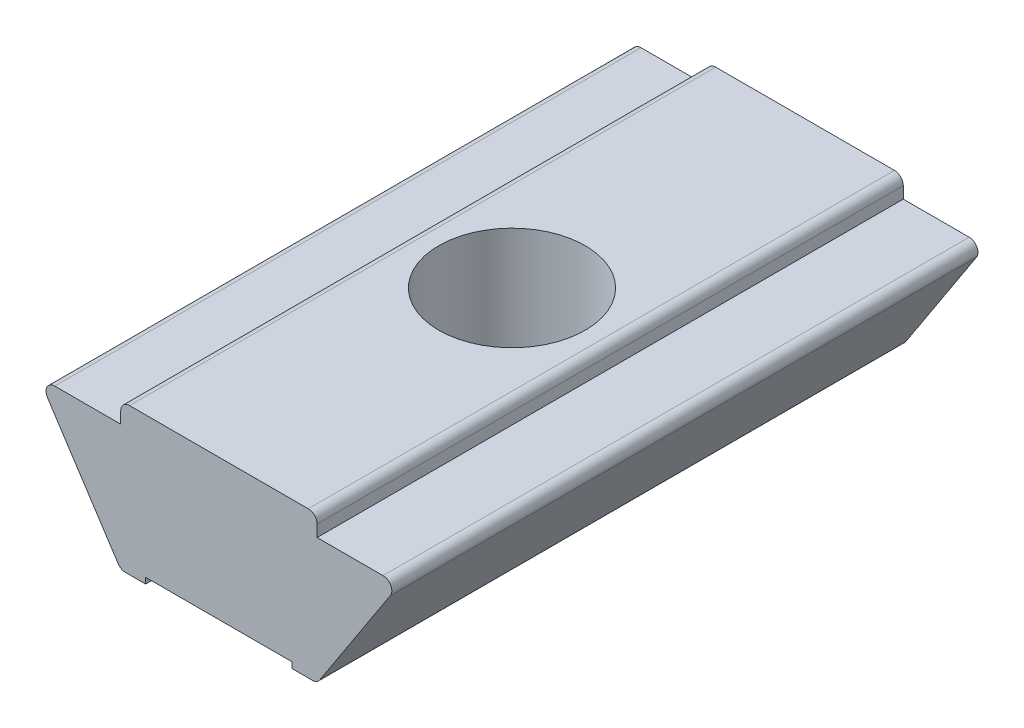
SolidWorks part; units mm, degrees
ref_plane "前视基准面" through (0, 0, 0) normal (0, 0, 1) x (1, 0, 0)
ref_plane "上视基准面" through (0, 0, 0) normal (0, 1, 0) x (1, 0, 0)
ref_plane "右视基准面" through (0, 0, 0) normal (1, 0, 0) x (0, 0, -1)
sketch "草图1" plane through (0, 0, 0) normal (0, 0, 1) x (1, 0, 0)
  line B0 (-0.1625, 4.7) -> (-0.1625, 4.3)
  line B1 (6.5375, 4.7) -> (6.5375, 4.3)
  line B2 (6.2375, 5) -> (0.1375, 5)
  line B3 (0, 0) -> (6.3749, 0)
  line B4 (-2.4125, 4.3) -> (-0.1625, 4.3)
  line B5 (6.5375, 4.3) -> (8.7875, 4.3)
  line B6 (-0.2513, 0.1362) -> (-2.6706, 3.847)
  line B7 (6.6262, 0.1362) -> (9.0455, 3.847)
  arc B8 (6.5375, 4.7) -> (6.2375, 5) centre (6.2375, 4.7) ccw
  arc B9 (0.1375, 5) -> (-0.1625, 4.7) centre (0.1375, 4.7) ccw
  arc B10 (-0.2513, 0.1362) -> (0, 0) centre (0, 0.3) ccw
  arc B11 (-2.4125, 4.3) -> (-2.6706, 3.847) centre (-2.4125, 4) ccw
  arc B12 (6.3749, 0) -> (6.6262, 0.1362) centre (6.3749, 0.3) ccw
  arc B13 (9.0455, 3.847) -> (8.7875, 4.3) centre (8.7875, 4) ccw
sketch_block_instance "A$C4175101B-1"
sketch_block "A$C4175101B"
extrude "凸台-拉伸1" add sketch "草图1" along normal mid plane 20
sketch "草图3" plane through (0, 5, 0) normal (0, 1, 0) x (1, 0, 0)
  line L0 (6.2375, 10) -> (0.1375, 10) construction
  point P0 (3.1875, 0)
  dimension "D1" = 10
hole_wizard "M6 螺纹孔1" positions "3D草图1" profile "草图4" tap size "M6" standard "Iso" end condition through all
sketch3d "3D草图1"
  point P0 (3.1875, 5, 0)
sketch "草图4" plane through (3.1875, 5, 0) normal (1, 0, 0) x (0, 0, 1)
  line L0 (0, 0) -> (0, 5)
  line L1 (0, 5) -> (2.5, 5)
  line L2 (2.5, 5) -> (2.5, 0)
  line L5 (2.5, 0) -> (0, 0)
  line L11 (0, -6.35) -> (0, 107.95) construction
  dimension "通孔螺纹孔钻头直径" = 5
  dimension "通孔螺纹孔钻头深度" = 5
cosmetic thread "孔螺蚊线1" parameters "D2"=6
sketch "草图5" plane through (0, 0, 10) normal (0, 0, 1) x (1, 0, 0)
  line L0 (0, 0) -> (6.3749, 0) construction
  line L1 (0.6875, 0) -> (5.6875, 0)
  line L2 (0.6875, 0) -> (0.6875, 0.2)
  line L3 (0.6875, 0.2) -> (5.6875, 0.2)
  line L4 (5.6875, 0) -> (5.6875, 0.2)
  line L5 (3.1875, 5) -> (3.1875, 0.2) construction
  line L6 (6.2375, 5) -> (0.1375, 5) construction
  dimension "D1" = 5
  dimension "D2" = 0.2
extrude "切除-拉伸1" cut sketch "草图5" against normal blind 10
ref_plane "基准面2" through (3.1875, 0, 0) normal (-1, 0, 0) x (0, 0, 1)
sketch "草图6" plane through (3.1875, 0, 0) normal (-1, 0, 0) x (0, 0, 1)
  line L0 (3.0032, 0.2) -> (-2.9988, -2.5)
  line L1 (0, 0.2) -> (10, 0.2) construction
  line L2 (10, 5) -> (-10, 5) construction
  line L3 (3.0032, 0.3097) -> (-3.0399, -2.4088)
  line L4 (3.0032, 0.2) -> (3.0032, 0.3097)
  line L5 (2.9621, 0.2912) -> (-3.0399, -2.4088) construction
  line L6 (-2.9988, -2.5) -> (-3.0399, -2.4088)
  dimension "D1" = 7.5
  dimension "D2" = 0.1
extrude "凸台-拉伸2" add sketch "草图6" along normal mid plane 5
sketch "草图7" plane through (0, -0.9573, 0.4306) normal (0, -0.912, 0.4103) x (1, 0, 0)
  line L1 (5.6875, 0.8308) -> (4.1563, -3.0083)
  line L3 (5.6875, -3.7605) -> (5.6875, 2.3333) construction
  line L4 (3.1875, -2.7605) -> (3.1875, -0.9062) construction
  line L5 (3.1875, 7.0269) -> (3.1875, -7.0269) construction
  line L6 (0.6875, 0.8308) -> (2.2186, -3.0083)
  line L7 (0.6875, 0.8308) -> (-4.8359, -0.2202)
  line L8 (-4.8359, -0.2202) -> (4.4182, -8.6714)
  line L9 (4.4182, -8.6714) -> (7.352, -1.6652)
  line L10 (7.352, -1.6652) -> (5.6875, 0.8308)
  arc A1 (2.2186, -3.0083) -> (4.1563, -3.0083) centre (3.1875, -2.7605) ccw
extrude "切除-拉伸2" cut sketch "草图7" against normal blind 0.3
